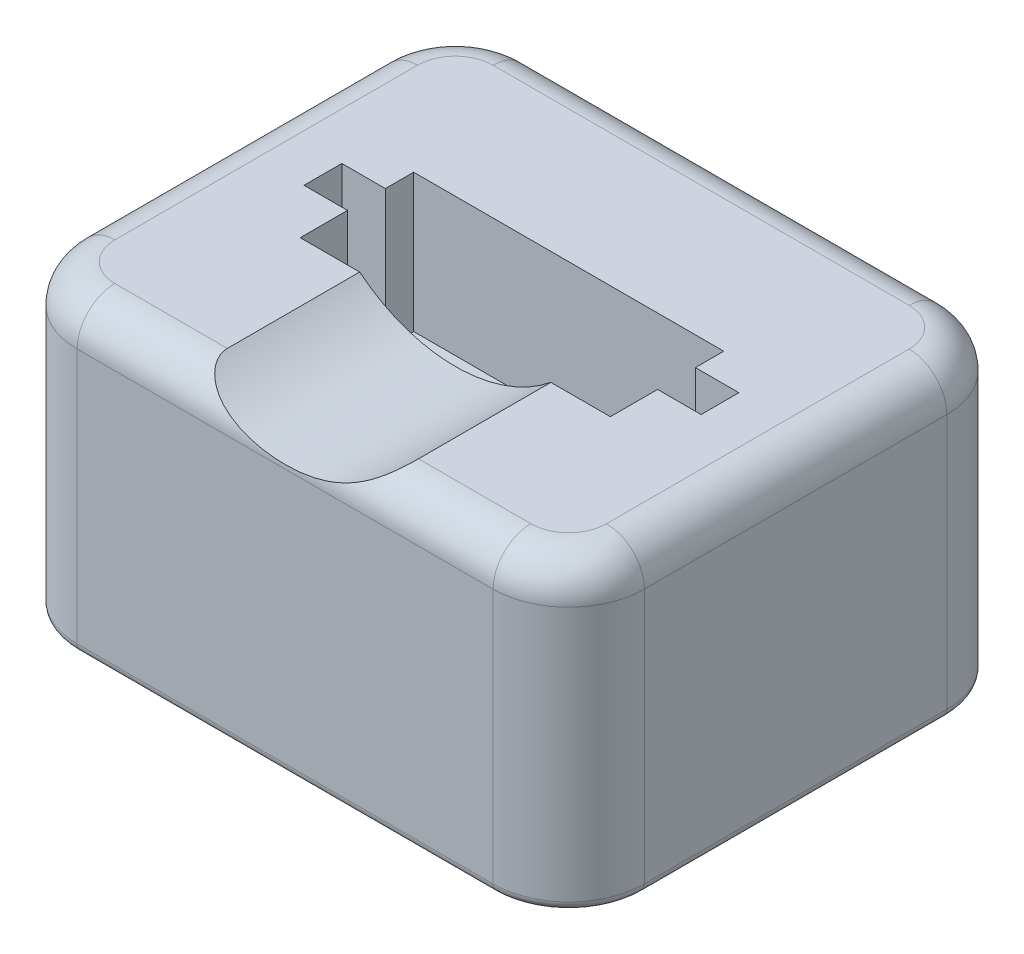
SolidWorks part; units mm, degrees
ref_plane "Спереди" through (0, 0, 0) normal (0, 0, 1) x (1, 0, 0)
ref_plane "Сверху" through (0, 0, 0) normal (0, 1, 0) x (1, 0, 0)
ref_plane "Справа" through (0, 0, 0) normal (1, 0, 0) x (0, 0, -1)
sketch "Эскиз1" plane through (0, 0, 0) normal (0, 1, 0) x (1, 0, 0)
  line L1 (4, 0) -> (26, 0)
  line L2 (0, 4) -> (0, 20)
  line L3 (4, 24) -> (26, 24)
  line L4 (30, 4) -> (30, 20)
  arc A0 (26, 24) -> (30, 20) centre (26, 20) cw
  arc A1 (26, 0) -> (30, 4) centre (26, 4) ccw
  arc A2 (4, 0) -> (0, 4) centre (4, 4) cw
  arc A3 (0, 20) -> (4, 24) centre (4, 20) cw
  point P10 (30, 0)
  point P13 (0, 0)
  point P16 (0, 24)
  dimension "D3" = 4
  dimension "D1" = 30
  dimension "D2" = 24
extrude "Бобышка-Вытянуть1" add sketch "Эскиз1" along normal blind 16
sketch "Эскиз6" plane through (0, 0, 0) normal (0, -1, 0) x (1, 0, 0)
  circle A0 centre (4, -4) radius 1
  circle A1 centre (26, -4) radius 1
  circle A2 centre (26, -20) radius 1
  circle A3 centre (4, -20) radius 1
  dimension "D1" = 2
extrude "Вырез-Вытянуть5" cut sketch "Эскиз6" against normal blind 7
fillet "Скругление2" radius 0.5 12 edges at (15, 0, -24) (1.1716, 0, -22.8284) (0, 0, -12) (1.1716, 0, -1.1716) (15, 0, 0) (28.8284, 0, -1.1716) (30, 0, -12) (28.8284, 0, -22.8284) (4, 0, -5) (26, 0, -5) (26, 0, -21) (4, 0, -21)
fillet "Скругление1" radius 2 8 edges at (15, 16, 0) (28.8284, 16, -1.1716) (1.1716, 16, -1.1716) (0, 16, -12) (1.1716, 16, -22.8284) (15, 16, -24) (28.8284, 16, -22.8284) (30, 16, -12)
sketch "Эскиз3" plane through (0, 16, 0) normal (0, 1, 0) x (1, 0, 0)
  line L1 (6.8, 12) -> (23.2, 12)
  line L2 (6.8, 12) -> (6.8, 9)
  line L3 (6.8, 9) -> (23.2, 9)
  line L4 (23.2, 12) -> (23.2, 9)
  line L5 (26, 0) -> (4, 0) construction
  point P4 (6.8, 10.5)
  point P5 (15, 9)
  point P6 (0, 0)
  point P10 (15, 0)
  dimension "D1" = 16.4
  dimension "D2" = 3
  dimension "D3" = 10.5
extrude "Вырез-Вытянуть1" cut sketch "Эскиз3" against normal up to next
sketch "Эскиз7" plane through (0, 16, 0) normal (0, 1, 0) x (1, 0, 0)
  line L1 (4.5, 11.5) -> (25.5, 11.5)
  line L2 (4.5, 11.5) -> (4.5, 13.5)
  line L3 (4.5, 13.5) -> (6.8, 13.5)
  line L4 (25.5, 11.5) -> (25.5, 13.5)
  line L5 (23.2, 12) -> (6.8, 12) construction
  line L7 (23.2, 13.5) -> (25.5, 13.5)
  line L9 (6.8, 13.5) -> (6.8, 15)
  line L10 (6.8, 15) -> (23.2, 15)
  line L11 (23.2, 13.5) -> (23.2, 15)
  line L12 (6.8, 12) -> (6.8, 9) construction
  point P6 (0, 0)
  point P7 (15, 12)
  point P12 (7.7295, 14.8)
  point P15 (4.5304, 12.9409)
  point P16 (15, 11.5)
  point P17 (4.4542, 11.4556)
  dimension "D1" = 3.5
  dimension "D2" = 21
  dimension "D3" = 2
  dimension "D4" = 0.5
extrude "Вырез-Вытянуть6" cut sketch "Эскиз7" against normal offset from surface (7.3 mm away) 8.7 up to face at (15, 0, -10.5)
sketch "Эскиз8" plane through (0, 0, 0) normal (0, 0, 1) x (1, 0, 0)
  line L0 (4, 0.5) -> (26, 0.5) construction
  circle A0 centre (15, 22.2) radius 8
  point P2 (0, 0)
  point P5 (15, 0.5)
  dimension "D1" = 16
  dimension "D2" = 22.2
extrude "Вырез-Вытянуть7" cut sketch "Эскиз8" against normal up to next
